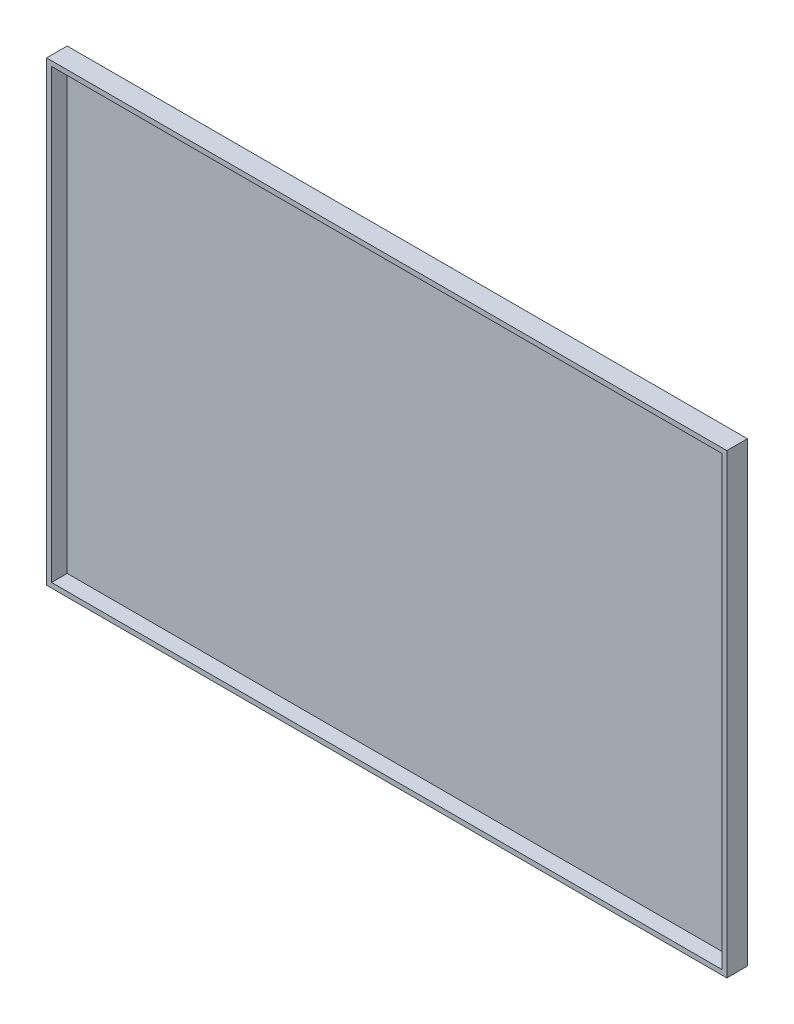
SolidWorks part; units mm, degrees
ref_plane "Plan de face" through (0, 0, 0) normal (0, 0, 1) x (1, 0, 0)
ref_plane "Plan de dessus" through (0, 0, 0) normal (0, 1, 0) x (1, 0, 0)
ref_plane "Plan de droite" through (0, 0, 0) normal (1, 0, 0) x (0, 0, -1)
sketch "Esquisse1" plane through (0, 0, 0) normal (0, 0, 1) x (1, 0, 0)
  line L1 (-3241.2789, 1394.3401) -> (-197.2789, 1394.3401)
  line L2 (-3241.2789, 1394.3401) -> (-3241.2789, -649.6599)
  line L3 (-3241.2789, -649.6599) -> (-197.2789, -649.6599)
  line L4 (-197.2789, 1394.3401) -> (-197.2789, -649.6599)
  dimension "D1" = 2044
  dimension "D2" = 3044
extrude "Boss.-Extru.1" add sketch "Esquisse1" along normal blind 92
sketch "Esquisse2" plane through (0, 0, 92) normal (0, 0, 1) x (1, 0, 0)
  line L0 (-3241.2789, 1394.3401) -> (-3241.2789, -649.6599) construction
  line L1 (-3219.2789, 1372.3401) -> (-219.2789, 1372.3401)
  line L2 (-3219.2789, 1372.3401) -> (-3219.2789, -627.6599)
  line L3 (-3219.2789, -627.6599) -> (-219.2789, -627.6599)
  line L4 (-219.2789, 1372.3401) -> (-219.2789, -627.6599)
  line L5 (-3241.2789, -649.6599) -> (-197.2789, -649.6599) construction
  dimension "D1" = 2000
  dimension "D2" = 3000
  dimension "D3" = 22
  dimension "D4" = 22
extrude "Enlèv. mat.-Extru.2" cut sketch "Esquisse2" against normal blind 70
